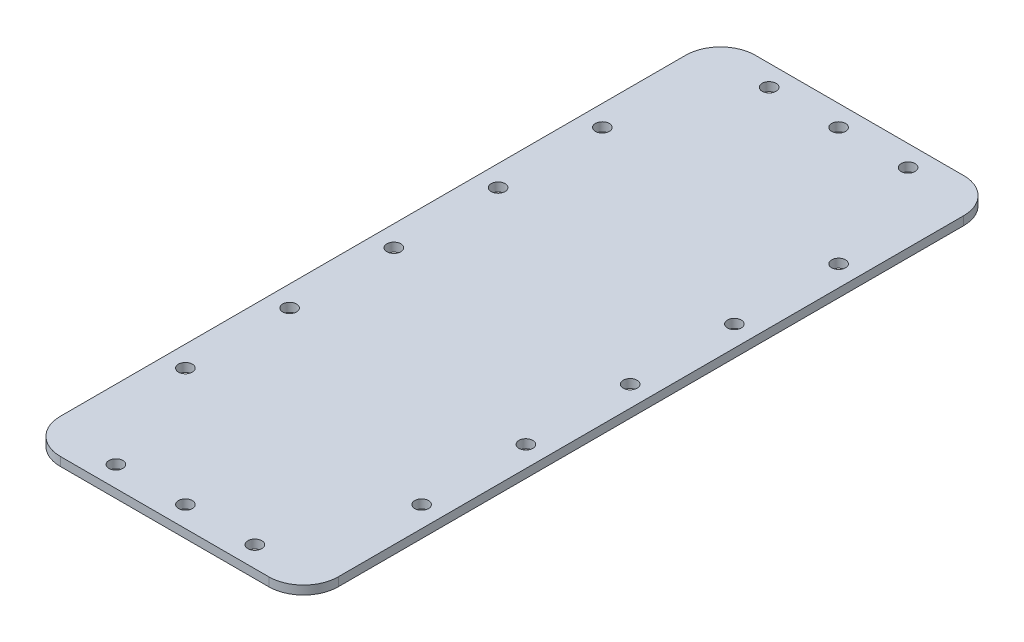
SolidWorks part; units mm, degrees
ref_plane "Front Plane" through (0, 0, 0) normal (0, 0, 1) x (1, 0, 0)
ref_plane "Top Plane" through (0, 0, 0) normal (0, 1, 0) x (1, 0, 0)
ref_plane "Right Plane" through (0, 0, 0) normal (1, 0, 0) x (0, 0, -1)
sketch "Sketch1" plane through (0, 0, 0) normal (0, 1, 0) x (1, 0, 0)
  line L0 (-157.6996, 42.9503) -> (197.9004, 42.9503) construction
  line L1 (-30.6996, 42.9503) -> (70.9004, 42.9503)
  line L2 (-30.6996, 42.9503) -> (-30.6996, -211.0497)
  line L3 (-30.6996, -211.0497) -> (70.9004, -211.0497)
  line L4 (70.9004, 42.9503) -> (70.9004, -211.0497)
  line L5 (-157.6996, -211.0497) -> (197.9004, -211.0497) construction
  dimension "D1" = 127
  dimension "D2" = 127
  dimension "D3" = 101.6
  dimension "D4" = 254
extrude "Boss-Extrude1" add sketch "Sketch1" along normal blind 3.175
sketch "Sketch2" plane through (0, 3.175, 0) normal (0, 1, 0) x (1, 0, 0)
  line L0 (20.1004, 42.9503) -> (20.1004, -50.0615) construction
  line L1 (70.9004, 42.9503) -> (-30.6996, 42.9503) construction
  line L2 (70.9004, -84.0497) -> (-81.795, -84.0497) construction
  line L3 (70.9004, -211.0497) -> (70.9004, 42.9503) construction
  line L4 (-30.6996, 42.9503) -> (-30.6996, -211.0497) construction
  circle A0 centre (-5.2996, 35.3303) radius 2.54
  circle A1 centre (20.1004, 35.3303) radius 2.54
  circle A2 centre (45.5004, 35.3303) radius 2.54
  circle A3 centre (-23.0796, -84.0497) radius 2.54
  circle A5 centre (-23.0796, -45.9497) radius 2.54
  circle A6 centre (-23.0796, -7.8497) radius 2.54
  circle A7 centre (63.2804, -7.8497) radius 2.54
  circle A8 centre (63.2804, -45.9497) radius 2.54
  circle A10 centre (63.2804, -84.0497) radius 2.54
  circle A12 centre (63.2804, -122.1497) radius 2.54
  circle A13 centre (63.2804, -160.2497) radius 2.54
  circle A14 centre (-23.0796, -160.2497) radius 2.54
  circle A15 centre (-23.0796, -122.1497) radius 2.54
  circle A17 centre (45.5004, -203.4297) radius 2.54
  circle A18 centre (20.1004, -203.4297) radius 2.54
  circle A19 centre (-5.2996, -203.4297) radius 2.54
  dimension "D3" = 5.08
  dimension "D4" = 5.08
  dimension "D5" = 5.08
  dimension "D10" = 5.08
  dimension "D11" = 5.08
  dimension "D12" = 5.08
  dimension "D1" = 25.4
  dimension "D2" = 25.4
  dimension "D6" = 38.1
  dimension "D8" = 38.1
  dimension "D13" = 7.62
  dimension "D14" = 7.62
extrude "Cut-Extrude1" cut sketch "Sketch2" against normal through all
fillet "Fillet1" radius 12.7 4 edges at (-30.6996, 1.5875, 211.0497) (70.9004, 1.5875, 211.0497) (70.9004, 1.5875, -42.9503) (-30.6996, 1.5875, -42.9503)
